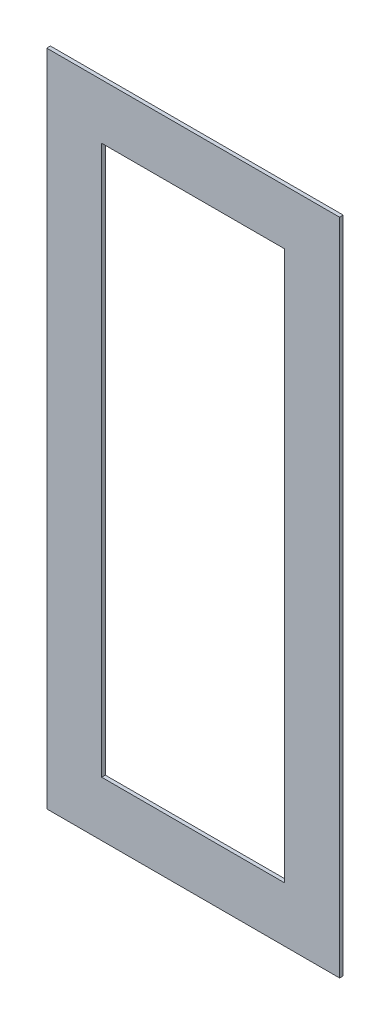
SolidWorks part; units mm, degrees
ref_plane "Front Plane" through (0, 0, 0) normal (0, 0, 1) x (1, 0, 0)
ref_plane "Top Plane" through (0, 0, 0) normal (0, 1, 0) x (1, 0, 0)
ref_plane "Right Plane" through (0, 0, 0) normal (1, 0, 0) x (0, 0, -1)
sketch "Sketch1" plane through (0, 0, 0) normal (0, 0, 1) x (1, 0, 0)
  line L0 (8, 18) -> (-8, 18)
  line L1 (5, 15) -> (-5, 15)
  line L2 (5, 15) -> (5, -15)
  line L3 (5, -15) -> (-5, -15)
  line L4 (-5, 15) -> (-5, -15)
  line L5 (5, 15) -> (-5, -15) construction
  line L6 (5, -15) -> (-5, 15) construction
  line L7 (-8, 18) -> (-8, -18)
  line L8 (8, -18) -> (-8, -18)
  line L9 (8, 18) -> (8, -18)
  point P0 (0, 0)
  dimension "D1" = 10
  dimension "D2" = 30
  dimension "D3" = 3
extrude "Boss-Extrude1" add sketch "Sketch1" along normal blind 0.2
